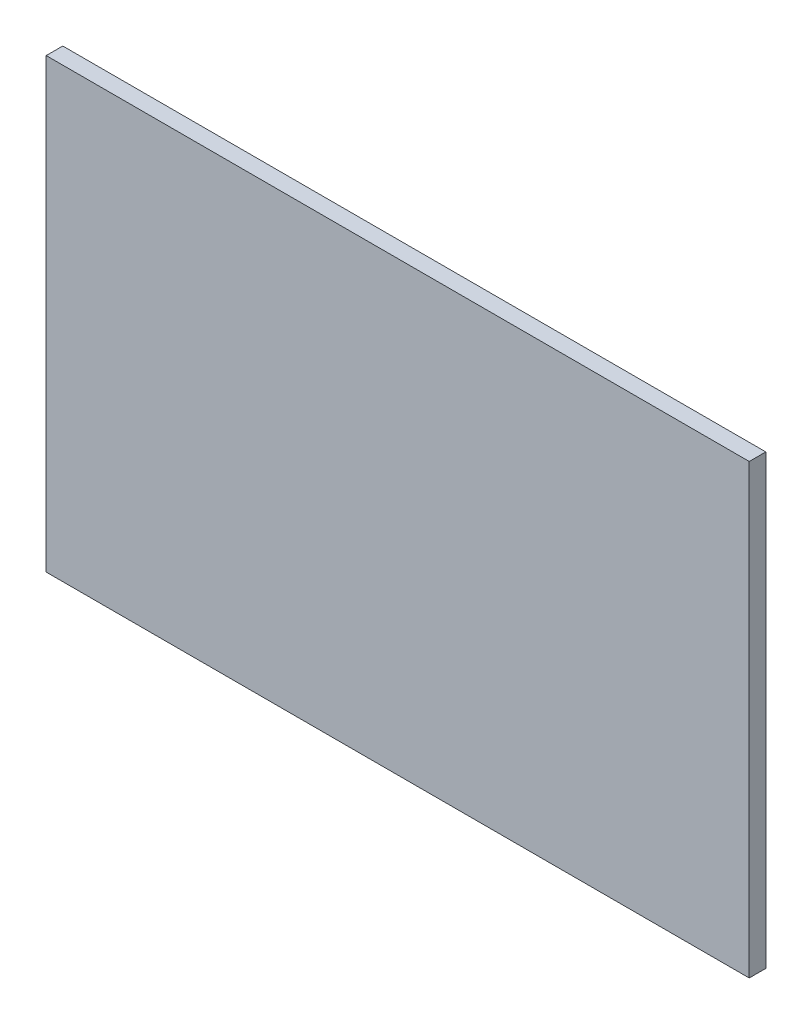
SolidWorks part; units mm, degrees
material "PPS"
ref_plane "Front Plane" through (0, 0, 0) normal (0, 0, 1) x (1, 0, 0)
ref_plane "Top Plane" through (0, 0, 0) normal (0, 1, 0) x (1, 0, 0)
ref_plane "Right Plane" through (0, 0, 0) normal (1, 0, 0) x (0, 0, -1)
sketch "Sketch1" plane through (0, 0, 0) normal (0, 0, 1) x (1, 0, 0)
  line L1 (0, 0) -> (63.65, 0)
  line L2 (0, 0) -> (0, 40.5)
  line L3 (0, 40.5) -> (63.65, 40.5)
  line L4 (63.65, 0) -> (63.65, 40.5)
  dimension "D1" = 63.65
  dimension "D2" = 40.5
extrude "Boss-Extrude1" add sketch "Sketch1" along normal blind 1.5
